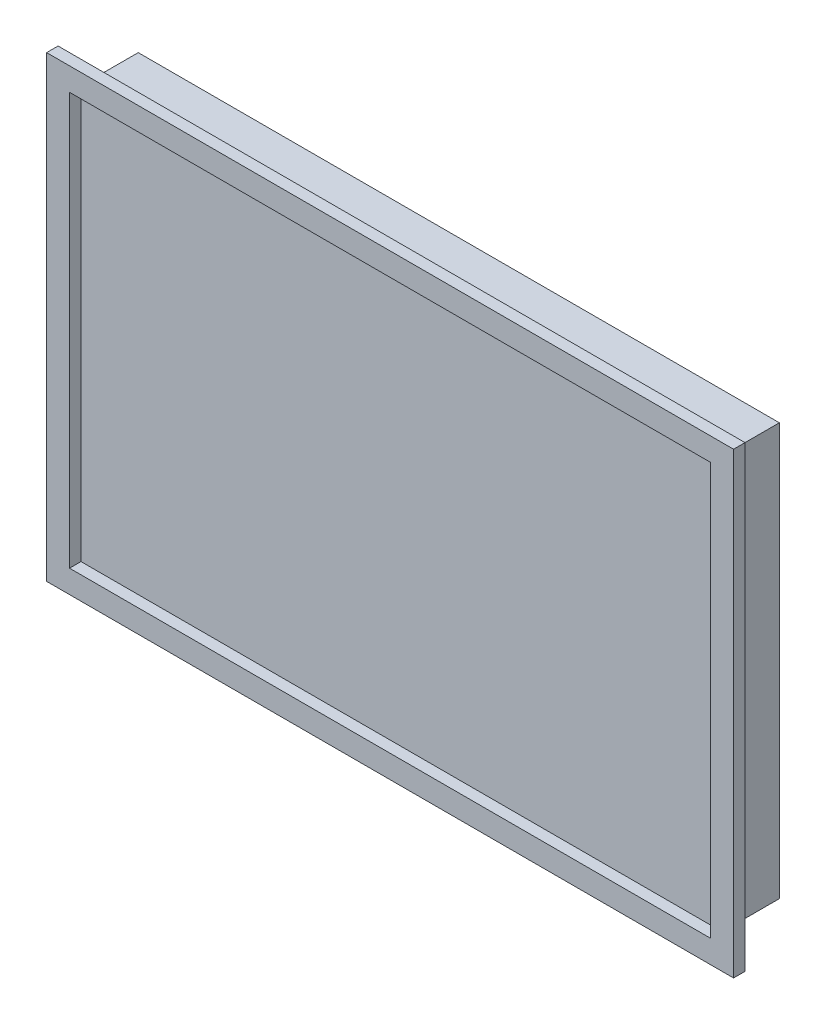
SolidWorks part; units mm, degrees
material "Q235A"
ref_plane "前视" through (0, 0, 0) normal (0, 0, 1) x (1, 0, 0)
ref_plane "上视" through (0, 0, 0) normal (0, 1, 0) x (1, 0, 0)
ref_plane "右视" through (0, 0, 0) normal (1, 0, 0) x (0, 0, -1)
sketch "草图1" plane through (0, 0, 0) normal (0, 0, 1) x (1, 0, 0)
  line L1 (150, -100) -> (-150, -100)
  line L2 (150, -100) -> (150, 100)
  line L3 (150, 100) -> (-150, 100)
  line L4 (-150, -100) -> (-150, 100)
  line L5 (150, -100) -> (-150, 100) construction
  line L6 (150, 100) -> (-150, -100) construction
  point P0 (0, 0)
  dimension "D1" = 300
  dimension "D2" = 200
extrude "凸台-拉伸1" add sketch "草图1" along normal blind 30
sketch "草图2" plane through (0, 0, 30) normal (0, 0, 1) x (1, 0, 0)
  line L0 (150, 100) -> (-150, 100) construction
  line L1 (140, -90) -> (-140, -90)
  line L2 (140, -90) -> (140, 90)
  line L3 (140, 90) -> (-140, 90)
  line L4 (-140, -90) -> (-140, 90)
  line L5 (140, -90) -> (-140, 90) construction
  line L6 (140, 90) -> (-140, -90) construction
  line L7 (-150, 100) -> (-150, -100) construction
  point P0 (0, 0)
  dimension "D1" = 10
  dimension "D2" = 10
extrude "切除-拉伸1" cut sketch "草图2" against normal blind 5
sketch "草图3" plane through (0, 0, 0) normal (0, 0, -1) x (-1, 0, 0)
  line L0 (-150, 100) -> (150, 100) construction
  line L1 (140, -90) -> (-140, -90)
  line L2 (140, -90) -> (140, 90)
  line L3 (140, 90) -> (-140, 90)
  line L4 (-140, -90) -> (-140, 90)
  line L5 (140, -90) -> (-140, 90) construction
  line L6 (140, 90) -> (-140, -90) construction
  line L7 (-150, -100) -> (-150, 100) construction
  point P0 (0, 0)
  dimension "D1" = 10
  dimension "D2" = 10
extrude "切除-拉伸2" cut sketch "草图3" against normal blind 25 flip side to cut
